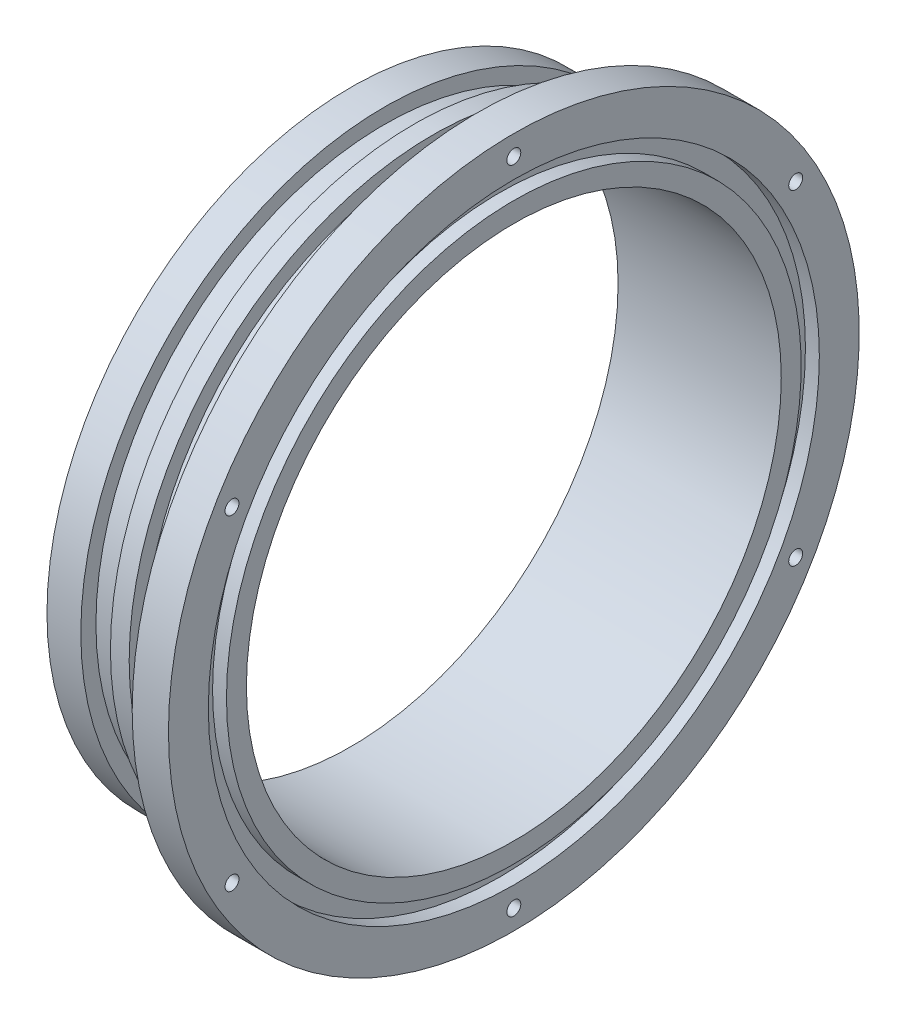
SolidWorks part; units mm, degrees
ref_plane "Plan de face" through (0, 0, 0) normal (0, 0, 1) x (1, 0, 0)
ref_plane "Plan de dessus" through (0, 0, 0) normal (0, 1, 0) x (1, 0, 0)
ref_plane "Plan de droite" through (0, 0, 0) normal (1, 0, 0) x (0, 0, -1)
sketch "Esquisse1" plane through (0, 0, 0) normal (0, 0, 1) x (1, 0, 0)
  line L0 (0, 0) -> (54.1477, 0) construction
  line L1 (0, 44.25) -> (27, 44.25)
  line L2 (27, 44.25) -> (27, 47.55)
  line L3 (27, 47.55) -> (24.7, 47.55)
  line L4 (24.7, 47.55) -> (24.7, 50.55)
  line L5 (24.7, 50.55) -> (27, 50.55)
  line L6 (27, 50.55) -> (27, 57.15)
  line L7 (27, 57.15) -> (21, 57.15)
  line L8 (21, 57.15) -> (21, 50.25)
  line L9 (21, 50.25) -> (18.4, 50.25)
  line L10 (18.4, 50.25) -> (18.4, 47.75)
  line L11 (18.4, 47.75) -> (13.6, 47.75)
  line L12 (13.6, 47.75) -> (13.6, 50.25)
  line L13 (13.6, 50.25) -> (10.5, 50.25)
  line L14 (10.5, 50.25) -> (10.5, 47.75)
  line L15 (10.5, 47.75) -> (5.6, 47.75)
  line L16 (5.6, 47.75) -> (5.6, 50.25)
  line L17 (5.6, 50.25) -> (0, 50.25)
  line L18 (0, 50.25) -> (0, 44.25)
  dimension "D1" = 27
  dimension "D2" = 12.9
  dimension "D3" = 3.3
  dimension "D4" = 3
  dimension "D5" = 2.3
  dimension "D6" = 6
  dimension "D8" = 5.6
  dimension "D9" = 13.6
  dimension "D10" = 3.1
  dimension "D11" = 4.9
  dimension "D12" = 4.8
  dimension "D13" = 2.5
  dimension "D14" = 44.25
  dimension "D15" = 57.15
  dimension "D16" = 50.25
revolve "Révolution1" add sketch "Esquisse1" angle 360 about L0
sketch "Esquisse2" plane through (27, 0, 0) normal (1, 0, 0) x (0, 0, -1)
  line L0 (0, 57.15) -> (0, 50.55) construction
  circle A0 centre (0, 0) radius 57.15 construction
  circle A1 centre (0, 0) radius 50.55 construction
  circle A2 centre (0, 0) radius 53.85 construction
  circle A3 centre (0, 53.85) radius 1.15
  circle A4 centre (46.6355, 26.925) radius 1.15
  circle A5 centre (46.6355, -26.925) radius 1.15
  circle A6 centre (0, -53.85) radius 1.15
  circle A7 centre (-46.6355, -26.925) radius 1.15
  circle A8 centre (-46.6355, 26.925) radius 1.15
  point P10 (0, 53.85)
  point P25 (0, 0)
  dimension "D1" = 2.3
  dimension "D3" = 107.7
  dimension "D2" = 6
extrude "Enlèv. mat.-Extru.1" cut sketch "Esquisse2" against normal through all
sketch "Esquisse3" plane through (0, 0, 0) normal (-1, 0, 0) x (0, 0, 1)
  line L0 (0, -50.25) -> (0, -44.25) construction
  circle A0 centre (0, 0) radius 50.25 construction
  circle A1 centre (0, 0) radius 50.25 construction
  circle A2 centre (0, 0) radius 44.25 construction
  circle A3 centre (0, -47) radius 1.15
  circle A4 centre (-47, 0) radius 1.15
  circle A5 centre (0, 47) radius 1.15
  circle A6 centre (47, 0) radius 1.15
  circle A7 centre (0, 0) radius 47 construction
  point P20 (0, 0)
  dimension "D1" = 2.3
  dimension "D3" = 94
  dimension "D2" = 4
extrude "Enlèv. mat.-Extru.2" cut sketch "Esquisse3" against normal blind 5
